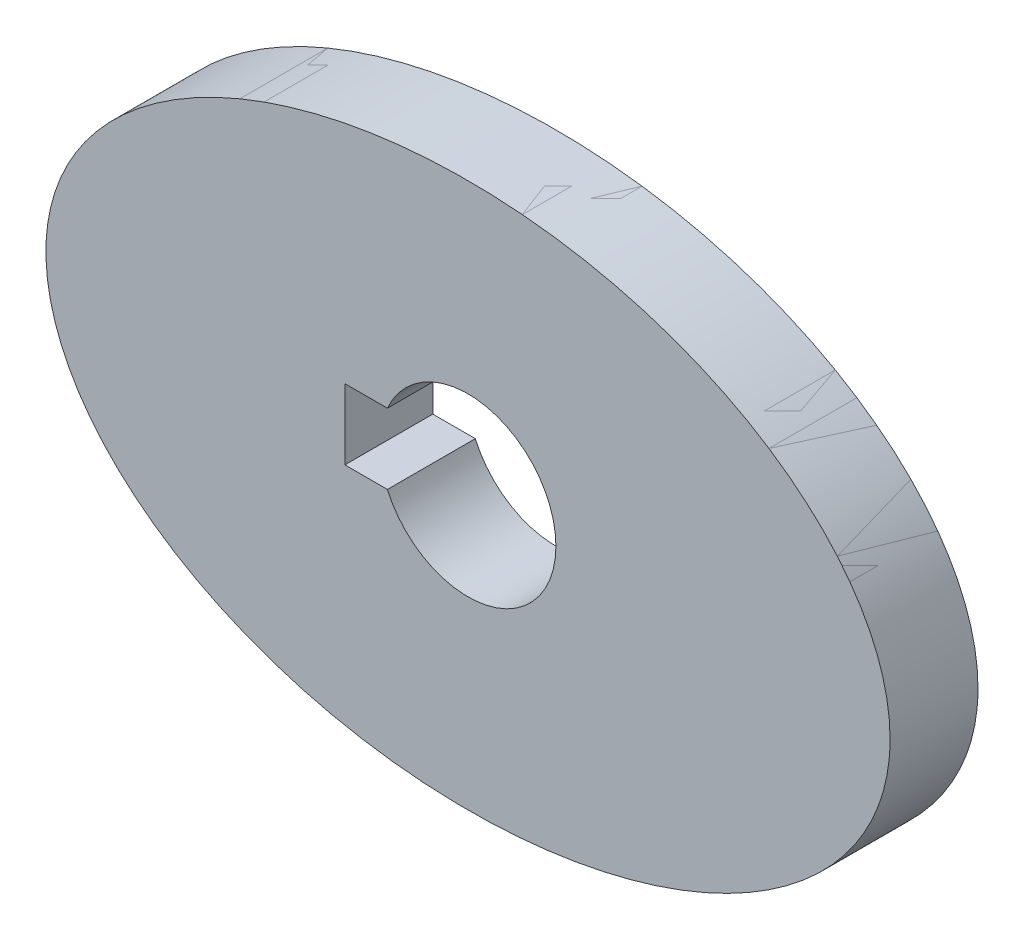
SolidWorks part; units mm, degrees
ref_plane "Alzado" through (0, 0, 0) normal (0, 0, 1) x (1, 0, 0)
ref_plane "Planta" through (0, 0, 0) normal (0, 1, 0) x (1, 0, 0)
ref_plane "Vista lateral" through (0, 0, 0) normal (1, 0, 0) x (0, 0, -1)
sketch "Croquis1" plane through (0, 0, 0) normal (0, 0, 1) x (1, 0, 0)
  line L1 (-7, 2) -> (-4.5826, 2)
  line L2 (-7, 2) -> (-7, -2)
  line L3 (-7, -2) -> (-4.5826, -2)
  arc A0 (-4.5826, -2) -> (-4.5826, 2) centre (0, 0) ccw
  ellipse E0 centre (0, 0) end of major axis (24, 0) minor radius 15.5
  point P3 (-7, 0)
  dimension "D1" = 10
  dimension "D2" = 48
  dimension "D3" = 15.5
  dimension "D4" = 7
  dimension "D5" = 4
extrude "Saliente-Extruir1" add sketch "Croquis1" along normal blind 5
sketch "Croquis2" plane through (0, 0, 5) normal (0, 0, 1) x (1, 0, 0)
  ellipse E0 centre (0, 0) end of major axis (24, 0) minor radius 15.5 construction
  ellipse E1 centre (0, 0) end of major axis (24, 0) minor radius 15.5
surface "Superficie-Extruir1" sketch "Croquis2" parameters "D1"=5
